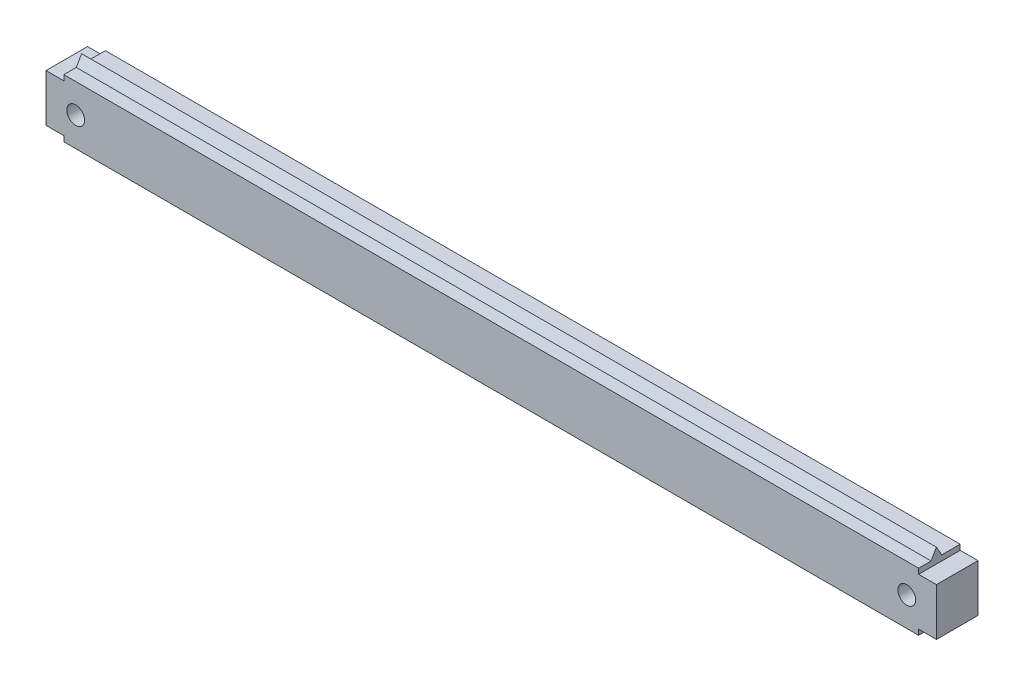
SolidWorks part; units mm, degrees
ref_plane "前视基准面" through (0, 0, 0) normal (0, 0, 1) x (1, 0, 0)
ref_plane "上视基准面" through (0, 0, 0) normal (0, 1, 0) x (1, 0, 0)
ref_plane "右视基准面" through (0, 0, 0) normal (1, 0, 0) x (0, 0, -1)
other "Configuration Table"
sketch "草图1" plane through (0, 0, 0) normal (0, 0, 1) x (1, 0, 0)
  line L1 (0, 0) -> (150, 0)
  line L2 (0, 0) -> (0, 18)
  line L3 (0, 18) -> (150, 18)
  line L4 (150, 0) -> (150, 18)
  dimension "D1" = 150
  dimension "D2" = 18
extrude "凸台-拉伸1" add sketch "草图1" along normal blind 7
sketch "草图2" plane through (150, 0, 0) normal (1, 0, 0) x (0, 0, -1)
  line L0 (-7, 13.9) -> (-4.9, 13.9)
  line L1 (-3.1, 4.1) -> (0, 4.1)
  line L2 (-4.9, 13.9) -> (-4, 15.4588)
  line L3 (-4, 2.5412) -> (-3.1, 4.1)
  line L4 (-4, 15.4588) -> (-3.1, 13.9)
  line L5 (-3.1, 13.9) -> (0, 13.9)
  line L6 (0, 9) -> (-50000, 9) construction
  line L7 (0, 0) -> (0, 18) construction
  line L8 (0, 0) -> (0, 18)
  line L9 (0, 18) -> (-7, 18)
  line L10 (-7, 18) -> (-7, 0)
  line L11 (-7, 0) -> (0, 0)
  line L12 (0, 4.1) -> (0, 13.9)
  line L14 (-7, 13.9) -> (-7, 4.1)
  line L16 (-4.9, 4.1) -> (-4, 2.5412)
  line L17 (-7, 4.1) -> (-4.9, 4.1)
  point P13 (0, 9)
  line M1 (0, 0) -> (0, 18)
  line M2 (0, 18) -> (-7, 18)
  line M3 (-7, 18) -> (-7, 0)
  line M4 (-7, 0) -> (0, 0)
  dimension "D1" = 0
  dimension "D2" = 4.9
  dimension "D3" = 2.1
  dimension "D4" = 60
  dimension "D5" = 120
  dimension "D6" = 1.8
sketch "草图3" plane through (0, 0, 7) normal (0, 0, 1) x (1, 0, 0)
  line L0 (0, 9) -> (-50000, 9) construction
  line L1 (0, 18) -> (0, 0) construction
  line L2 (75, 18) -> (75, -49982) construction
  line L3 (150, 18) -> (0, 18) construction
  circle A0 centre (5, 9) radius 1.5
  circle A1 centre (145, 9) radius 1.5
  point P4 (0, 9)
  point P9 (75, 18)
  dimension "D1" = 3
  dimension "D2" = 140
extrude "切除-拉伸1" cut sketch "草图3" against normal up to next
extrude "切除-拉伸2" cut sketch "草图2" against normal up to next contours L4 L5 L0 L2 M1 M2 M3 | L17 L1 L3 L16 M3 M4 M1
sketch "草图5" plane through (0, 0, 7) normal (0, 0, 1) x (1, 0, 0)
  line L6 (0, 9) -> (-50000, 9) construction
  line L7 (0, 13.9) -> (0, 4.1) construction
  line L8 (75, 15.4588) -> (75, 50015.4588) construction
  line L9 (0, 5) -> (3, 5) construction
  line L10 (0, 5) -> (0, 13) construction
  line L11 (0, 13) -> (3, 13) construction
  line L12 (3, 5) -> (3, 13) construction
  line L13 (0, 15.4588) -> (150, 15.4588) construction
  line L18 (3, 13) -> (3, 15.4588)
  line L19 (3, 15.4588) -> (0, 15.4588)
  line L20 (0, 15.4588) -> (0, 13)
  line L21 (0, 13) -> (3, 13)
  line L22 (0, 5) -> (0, 2.5412)
  line L23 (0, 2.5412) -> (3, 2.5412)
  line L24 (0, 2.5412) -> (150, 2.5412) construction
  line L25 (3, 2.5412) -> (3, 5)
  line L26 (3, 5) -> (0, 5)
  line L27 (147, 5) -> (147, 13) construction
  line L28 (150, 13) -> (147, 13) construction
  line L29 (150, 5) -> (150, 13) construction
  line L30 (150, 5) -> (147, 5) construction
  line L31 (147, 5) -> (150, 5)
  line L32 (147, 2.5412) -> (147, 5)
  line L33 (150, 2.5412) -> (147, 2.5412)
  line L34 (150, 5) -> (150, 2.5412)
  line L35 (150, 13) -> (147, 13)
  line L36 (150, 15.4588) -> (150, 13)
  line L37 (147, 15.4588) -> (150, 15.4588)
  line L38 (147, 13) -> (147, 15.4588)
  point P4 (0, 9)
  point P11 (0, 9)
  point P17 (75, 15.4588)
  dimension "D1" = 8
  dimension "D2" = 3
extrude "切除-拉伸3" cut sketch "草图5" against normal up to next
sketch "草图6" plane through (0, 0, 0) normal (0, 0, -1) x (-1, 0, 0)
  line L0 (-75, 13.9) -> (-75, -49986.1) construction
  line L1 (-3, 13.9) -> (-147, 13.9) construction
  line L2 (0, 9) -> (50000, 9) construction
  line L3 (0, 13) -> (0, 5) construction
  line L4 (-105, 9) -> (-45, 9)
  circle A0 centre (-105, 9) radius 3
  circle A1 centre (-45, 9) radius 3
  point P4 (-75, 13.9)
  point P9 (0, 9)
  point P12 (-75, 9)
  dimension "D2" = 6
  dimension "D3" = 6
  dimension "D1" = 60
extrude "切除-拉伸4" cut sketch "草图6" against normal blind 3
